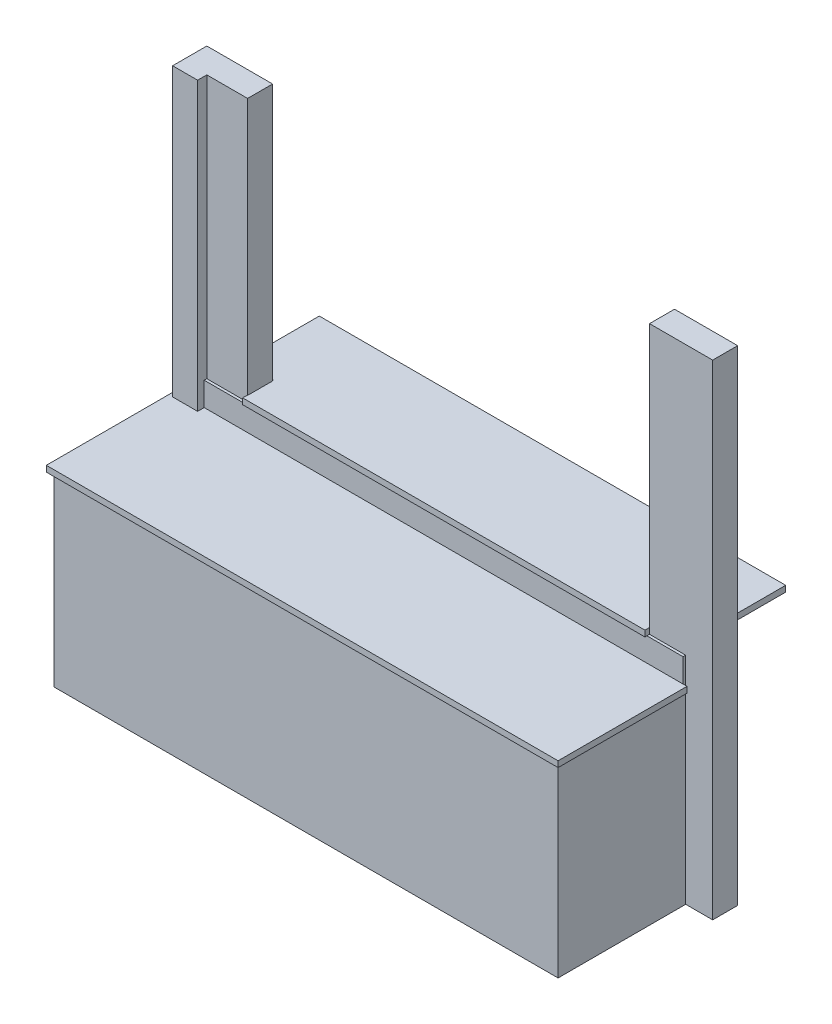
SolidWorks part; units mm, degrees
ref_plane "Front Plane" through (0, 0, 0) normal (0, 0, 1) x (1, 0, 0)
ref_plane "Top Plane" through (0, 0, 0) normal (0, 1, 0) x (1, 0, 0)
ref_plane "Right Plane" through (0, 0, 0) normal (1, 0, 0) x (0, 0, -1)
sketch "Sketch1" plane through (0, 0, 0) normal (0, 1, 0) x (1, 0, 0)
  line L1 (-1235.075, 311.15) -> (1235.075, 311.15)
  line L2 (-1235.075, 311.15) -> (-1235.075, -311.15)
  line L3 (-1235.075, -311.15) -> (1235.075, -311.15)
  line L4 (1235.075, 311.15) -> (1235.075, -311.15)
  line L5 (-1235.075, 311.15) -> (1235.075, -311.15) construction
  line L6 (-1235.075, -311.15) -> (1235.075, 311.15) construction
  point P0 (0, 0)
  dimension "D1" = 2470.15
  dimension "D2" = 622.3
extrude "Boss-Extrude1" add sketch "Sketch1" against normal blind 28.575
sketch "Sketch2" plane through (0, -28.575, 0) normal (0, -1, 0) x (1, 0, 0)
  line L0 (-1235.075, 311.15) -> (1235.075, 311.15) construction
  line L1 (-1216.025, 292.1) -> (1216.025, 292.1)
  line L2 (-1216.025, 292.1) -> (-1216.025, -444.5)
  line L3 (-1216.025, -444.5) -> (1216.025, -444.5)
  line L4 (1216.025, 292.1) -> (1216.025, -444.5)
  line L5 (-1235.075, -311.15) -> (-1235.075, 311.15) construction
  line L6 (1235.075, 311.15) -> (1235.075, -311.15) construction
  dimension "D1" = 19.05
  dimension "D2" = 19.05
  dimension "D3" = 19.05
  dimension "D4" = 736.6
extrude "Boss-Extrude2" add sketch "Sketch2" along normal blind 898.525
sketch "Sketch3" plane through (0, -28.575, 0) normal (0, 1, 0) x (1, 0, 0)
  line L1 (1216.025, 311.15) -> (-1216.025, 311.15)
  line L2 (1216.025, 311.15) -> (1216.025, 444.5)
  line L3 (1216.025, 444.5) -> (-1216.025, 444.5)
  line L4 (-1216.025, 311.15) -> (-1216.025, 444.5)
extrude "Boss-Extrude3" add sketch "Sketch3" along normal offset from surface (142.875 mm away) 1041.4 up to face at (0, -927.1, -76.2)
sketch "Sketch4" plane through (0, 114.3, 0) normal (0, 1, 0) x (1, 0, 0)
  line L0 (-1216.025, 311.15) -> (-1216.025, 444.5) construction
  line L1 (-1057.275, 828.675) -> (1193.8, 828.675)
  line L2 (-1057.275, 828.675) -> (-1057.275, 450.85)
  line L3 (-900.1125, 301.625) -> (1041.4, 301.625)
  line L4 (1193.8, 828.675) -> (1193.8, 450.85)
  line L5 (1216.025, 311.15) -> (-1216.025, 311.15) construction
  line L6 (-1057.275, 450.85) -> (-900.1125, 450.85)
  line L7 (-900.1125, 450.85) -> (-900.1125, 301.625)
  line L8 (1041.4, 301.625) -> (1041.4, 450.85)
  line L9 (1041.4, 450.85) -> (1193.8, 450.85)
  dimension "D1" = 2251.075
  dimension "D2" = 158.75
  dimension "D3" = 9.525
  dimension "D4" = 527.05
  dimension "D5" = 157.1625
  dimension "D6" = 149.225
  dimension "D7" = 152.4
  dimension "D8" = 149.225
extrude "Boss-Extrude4" add sketch "Sketch4" along normal blind 28.575
sketch "Sketch5" plane through (0, 114.3, 0) normal (0, 1, 0) x (1, 0, 0)
  line L0 (-1216.025, 444.5) -> (-1216.025, 279.4)
  line L1 (-1216.025, 279.4) -> (-1095.375, 279.4)
  line L2 (-1095.375, 279.4) -> (-1095.375, 323.85)
  line L3 (-1095.375, 323.85) -> (-898.525, 323.85)
  line L4 (-898.525, 323.85) -> (-898.525, 444.5)
  line L5 (-898.525, 444.5) -> (-1216.025, 444.5)
  dimension "D1" = 317.5
  dimension "D2" = 165.1
  dimension "D3" = 120.65
  dimension "D4" = 120.65
extrude "Boss-Extrude5" add sketch "Sketch5" along normal blind 1270 and the other way up to surface other way up to face at (0, 0, -103.7167)
sketch "Sketch6" plane through (0, 142.875, 0) normal (0, 1, 0) x (1, 0, 0)
  line L1 (1041.4, 444.5) -> (1346.2, 444.5)
  line L2 (1041.4, 444.5) -> (1041.4, 323.85)
  line L3 (1041.4, 323.85) -> (1346.2, 323.85)
  line L4 (1346.2, 444.5) -> (1346.2, 323.85)
  line L5 (1193.8, 450.85) -> (1193.8, 828.675) construction
  line L6 (-900.1125, 444.5) -> (1041.4, 444.5) construction
  dimension "D1" = 304.8
  dimension "D2" = 120.65
  dimension "D4" = 152.4
extrude "Boss-Extrude6" add sketch "Sketch6" along normal blind 1270 and the other way up to surface (1069.975 mm away) other way up to face at (0, -927.1, -76.2)
equation "\"D1@Boss-Extrude2\"=36.5 - 1:1/8"
equation "\"D4@Sketch5\"=\"D3@Sketch5\""
